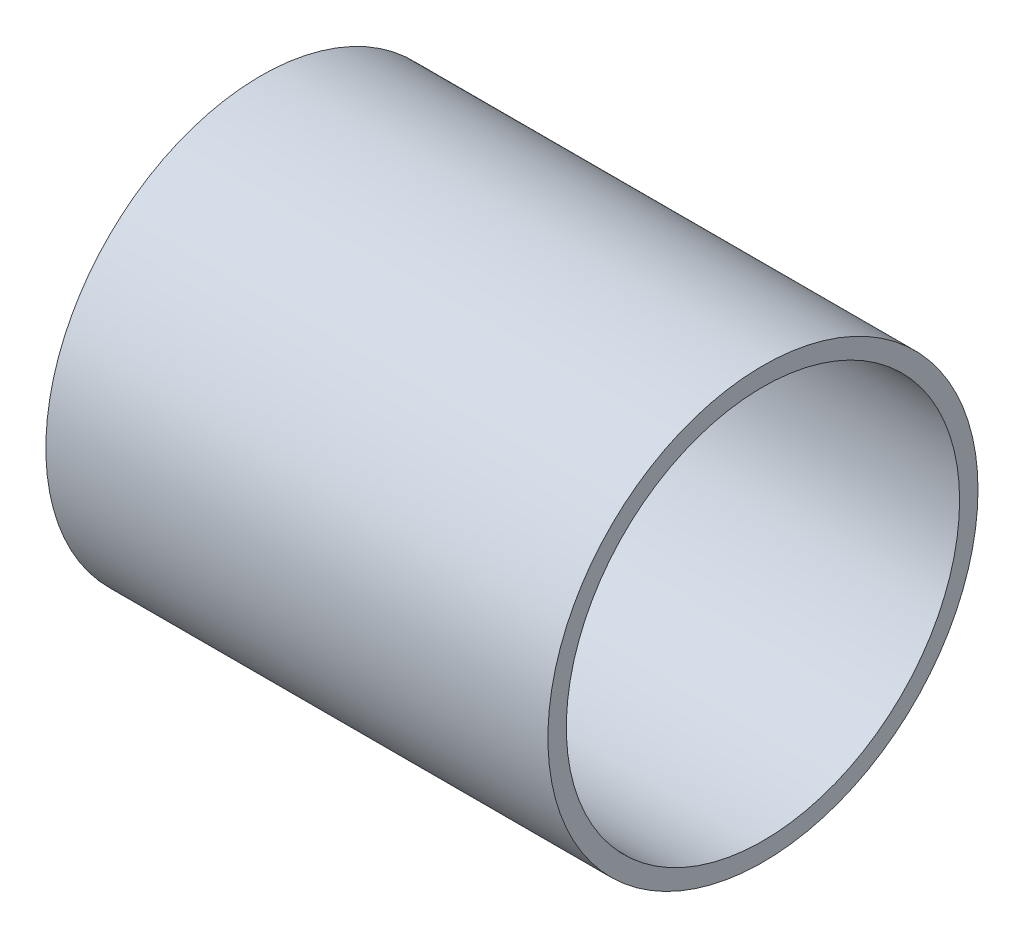
SolidWorks part; units mm, degrees
ref_plane "Спереди" through (0, 0, 0) normal (0, 0, 1) x (1, 0, 0)
ref_plane "Сверху" through (0, 0, 0) normal (0, 1, 0) x (1, 0, 0)
ref_plane "Справа" through (0, 0, 0) normal (1, 0, 0) x (0, 0, -1)
sketch "Эскиз1" plane through (0, 0, 0) normal (1, 0, 0) x (0, 0, -1)
  circle A0 centre (0, 0) radius 11.75
  circle A1 centre (0, 0) radius 12.85
  dimension "D1" = 23.5
  dimension "D2" = 25.7
extrude "Бобышка-Вытянуть1" add sketch "Эскиз1" along normal blind 30
